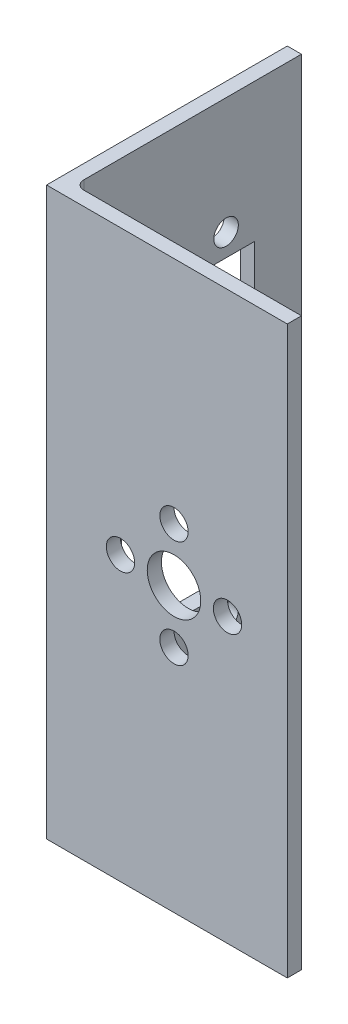
SolidWorks part; units mm, degrees
material "6061-T6 (SS)"
ref_plane "Front Plane" through (0, 0, 0) normal (0, 0, 1) x (1, 0, 0)
ref_plane "Top Plane" through (0, 0, 0) normal (0, 1, 0) x (1, 0, 0)
ref_plane "Right Plane" through (0, 0, 0) normal (1, 0, 0) x (0, 0, -1)
sketch "Sketch1" plane through (0, 0, 0) normal (0, 1, 0) x (1, 0, 0)
  line L0 (0, 50.8) -> (0, 0)
  line L1 (0, 0) -> (50.8, 0)
  line L2 (-3.175, 50.8) -> (-3.175, -3.175)
  line L3 (-3.175, -3.175) -> (50.8, -3.175)
  line L4 (-3.175, 50.8) -> (0, 50.8)
  line L5 (50.8, 0) -> (50.8, -3.175)
  dimension "D1" = 50.8
  dimension "D2" = 50.8
  dimension "D3" = 3.175
extrude "Boss-Extrude1" add sketch "Sketch1" along normal blind 127
sketch "Sketch2" plane through (0, 0, 0) normal (0, 0, -1) x (-1, 0, 0)
  line L0 (-50.8, 127) -> (0, 127) construction
  line L1 (-50.8, 127) -> (-50.8, 0) construction
  circle A0 centre (-25.4, 63.5) radius 6
  circle A8 centre (-25.4, 75.5) radius 3.175
  circle A9 centre (-13.4, 63.5) radius 3.175
  circle A10 centre (-25.4, 51.5) radius 3.175
  circle A11 centre (-37.4, 63.5) radius 3.175
  point P5 (-25.4, 127)
  point P8 (-50.8, 63.5)
  point P17 (-25.4, 63.5)
  point P27 (-25.4, 63.5)
  dimension "D1" = 12
  dimension "D2" = 6.35
  dimension "D3" = 4
  dimension "D4" = 12
extrude "Cut-Extrude1" cut sketch "Sketch2" against normal up to next
sketch "Sketch3" plane through (0, 0, 0) normal (1, 0, 0) x (0, 0, -1)
  line L4 (50.8, 127) -> (50.8, 0) construction
  line L9 (10.5, 63.5) -> (40.3, 63.5) construction
  line L10 (33.9, 100.9) -> (16.9, 100.9) construction
  line L11 (10.5, 31.1) -> (40.3, 31.1)
  line L12 (40.3, 95.9) -> (40.3, 31.1)
  line L13 (10.5, 95.9) -> (40.3, 95.9)
  line L14 (10.5, 95.9) -> (10.5, 31.1)
  circle A6 centre (33.9, 100.9) radius 2.75
  circle A7 centre (16.9, 100.9) radius 2.75
  circle A8 centre (16.9, 26.1) radius 2.75
  circle A9 centre (33.9, 26.1) radius 2.75
  point P1 (25.4, 100.9)
  point P2 (25.4, 63.5)
  point P9 (50.8, 63.5)
  dimension "D3" = 64.8
  dimension "D1" = 5.5
  dimension "D2" = 5
  dimension "D4" = 29.8
  dimension "D5" = 17
extrude "Cut-Extrude2" cut sketch "Sketch3" against normal up to next
fillet "Fillet1" radius 2 1 edges at (0, 63.5, 0)
